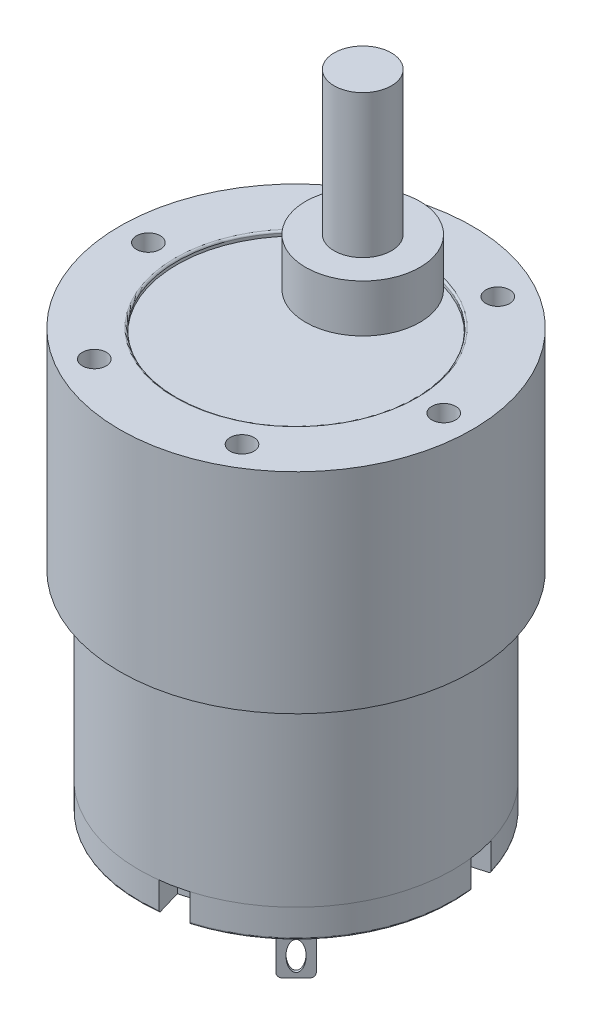
SolidWorks part; units mm, degrees
ref_plane "前视" through (0, 0, 0) normal (0, 0, 1) x (1, 0, 0)
ref_plane "上视" through (0, 0, 0) normal (0, 1, 0) x (1, 0, 0)
ref_plane "右视" through (0, 0, 0) normal (1, 0, 0) x (0, 0, -1)
sketch "草图1" plane through (0, 0, 0) normal (0, 0, 1) x (1, 0, 0)
  line L0 (0, -0.5) -> (0, -44)
  line L1 (16.5, -41) -> (16.48, -41)
  line L2 (16.5, -41) -> (16.5, -22)
  line L5 (16.5, -22) -> (18.5, -22)
  line L6 (18.5, -22) -> (18.5, 0)
  line L7 (18.5, 0) -> (12.7, 0)
  line L8 (12.5, -0.2) -> (12.5, -0.5)
  line L9 (12.5, -0.5) -> (0, -0.5)
  line L10 (16.48, -41) -> (16.48, -43.8)
  line L11 (16.28, -44) -> (0, -44)
  arc A0 (16.48, -43.8) -> (16.28, -44) centre (16.28, -43.8) cw
  arc A1 (12.5, -0.2) -> (12.7, 0) centre (12.7, -0.2) cw
  point P3 (16.5, -18.6359)
  point P4 (16.2721, -41.5113)
  point P6 (16.48, -44)
  dimension "D8" = 0.2
  dimension "D14" = 0.2
  dimension "D2" = 19
  dimension "D3" = 3
  dimension "D4" = 0.02
  dimension "D5" = 18.5
  dimension "D6" = 16.5
  dimension "D7" = 22
  dimension "D11" = 0.5
  dimension "D12" = 12.5
revolve "旋转1" add sketch "草图1" angle 360 about L0
hole_wizard "M3 螺纹孔1" positions "草图3" profile "草图2" tap size "M3" standard "GB"
sketch "草图3" plane through (0, 0, 0) normal (0, 1, 0) x (1, 0, 0)
  line L0 (18.5, 0) -> (-18.5, 0) construction
  circle A0 centre (0, 0) radius 18.5 construction
  circle A1 centre (0, 0) radius 15.5 construction
  point P0 (-15.5, 0)
  dimension "D1" = 31
sketch "草图2" plane through (-15.5, 0, 0) normal (1, 0, 0) x (0, 0, 1)
  line L0 (0, 0) -> (0, 9.2511)
  line L1 (0, 9.2511) -> (1.25, 8.5)
  line L2 (1.25, 8.5) -> (1.25, 0)
  line L5 (1.25, 0) -> (0, 0)
  line L10 (0, 9.2511) -> (-1.25, 8.5) construction
  line L11 (0, -6.35) -> (0, 107.95) construction
  dimension "螺纹孔钻头直径" = 2.5
  dimension "螺纹孔钻头深度" = 8.5
  dimension "导头角度" = 118
cosmetic thread "孔螺蚊线1" parameters "D1"=6, "D2"=3
pattern_circular "阵列(圆周)1" count 6 over 360 about axis through (0, 0, 0) along (0, 1, 0) of "M3 螺纹孔1"
sketch "草图4" plane through (0, 0, 0) normal (0, 1, 0) x (1, 0, 0)
  line L0 (0, 18.5) -> (0, -18.5) construction
  line L1 (-18.5, 0) -> (18.5, 0) construction
  circle A0 centre (0, 0) radius 18.5 construction
  circle A1 centre (0, 7) radius 6
  dimension "D1" = 12
  dimension "D2" = 7
extrude "凸台-拉伸1" add sketch "草图4" along normal blind 5
sketch "草图5" plane through (0, 5, 0) normal (0, 1, 0) x (1, 0, 0)
  circle A0 centre (0, 7) radius 3
  dimension "D1" = 6
extrude "凸台-拉伸2" add sketch "草图5" along normal blind 15
sketch "草图6" plane through (0, -44, 0) normal (0, -1, 0) x (1, 0, 0)
  circle A0 centre (0, 0) radius 3.75
  dimension "D1" = 7.5
extrude "凸台-拉伸3" add sketch "草图6" along normal blind 3
sketch "草图7" plane through (0, -47, 0) normal (0, -1, 0) x (1, 0, 0)
  circle A0 centre (0, 0) radius 1
  dimension "D1" = 2
extrude "凸台-拉伸4" add sketch "草图7" along normal blind 7
sketch "草图8" plane through (0, -44, 0) normal (0, -1, 0) x (1, 0, 0)
  line L0 (-18.5, 0) -> (18.5, 0) construction
  line L1 (0, 18.5) -> (0, -18.5) construction
  line L2 (-4.6748, -15.8031) -> (-3.8142, -12.8938)
  line L3 (-3.8142, -12.8938) -> (-1.2008, -13.6669)
  line L4 (-1.2008, -13.6669) -> (-1.997, -16.3586)
  circle A0 centre (0, 0) radius 18.5 construction
  arc A3 (-4.6748, -15.8031) -> (-1.997, -16.3586) centre (0, 0) ccw
extrude "切除-拉伸1" cut sketch "草图8" against normal blind 3
pattern_circular "阵列(圆周)2" count 4 over 360 about axis through (0, 0, 0) along (0, 1, 0) of "切除-拉伸1"
sketch "草图9" plane through (0, -44, 0) normal (0, -1, 0) x (1, 0, 0)
  line L0 (-8.4853, -8.4853) -> (8.4853, 8.4853) construction
  line L1 (0, 0) -> (13.0815, -13.0815) construction
  line L2 (0, -18.6657) -> (0, 18.5) construction
  line L3 (-9.4399, -7.3186) -> (-7.3186, -9.4399)
  line L4 (-7.3186, -9.4399) -> (-7.5307, -9.652)
  line L5 (-7.5307, -9.652) -> (-9.652, -7.5307)
  line L6 (-9.652, -7.5307) -> (-9.4399, -7.3186)
  line L7 (-9.5459, -7.4246) -> (-7.4246, -9.5459) construction
  line L8 (7.5307, 9.652) -> (7.3186, 9.4399)
  line L9 (9.652, 7.5307) -> (7.5307, 9.652)
  line L10 (9.4399, 7.3186) -> (9.652, 7.5307)
  line L11 (7.3186, 9.4399) -> (9.4399, 7.3186)
  circle A0 centre (0, 0) radius 18.5 construction
  dimension "D1" = 3
  dimension "D2" = 0.3
  dimension "D3" = 24
  dimension "D4" = 45
extrude "凸台-拉伸5" add sketch "草图9" along normal blind 6.5
sketch "草图10" plane through (-8.5913, 0, -8.5913) normal (-0.7071, 0, -0.7071) x (-0.7071, 0, 0.7071)
  line L0 (-1.5, -50.5) -> (1.5, -50.5) construction
  line L1 (1.5, -50.5) -> (-1.5, -50.5) construction
  line L2 (0, -50.5) -> (0, -44) construction
  line L3 (1.5, -44) -> (-1.5, -44) construction
  ellipse E0 centre (0, -48.5) end of major axis (0, -50) minor radius 0.75
  dimension "D1" = 3
  dimension "D2" = 1.5
  dimension "D3" = 3
extrude "切除-拉伸2" cut sketch "草图10" against normal blind 3
fillet "圆角1" radius 0.5 4 edges at (-9.5459, -50.5, -7.4246) (-7.4246, -50.5, -9.5459) (7.4246, -50.5, 9.5459) (9.5459, -50.5, 7.4246)
ref_plane "基准面1" through (0, 0, 0) normal (-0.7071, 0, -0.7071) x (-0.7071, 0, 0.7071)
mirror "镜向5" about plane through (0, 0, 0) normal (-0.7071, 0, -0.7071) of "切除-拉伸2"
ref_plane "基准面2" [suppressed] through (0, -45, 0) normal (0, -1, 0) x (-1, 0, 0)
sketch "草图11" [suppressed] plane through (0, -45, 0) normal (0, -1, 0) x (-1, 0, 0)
  circle A0 centre (0, 0) radius 16.5
  circle A1 centre (0, 0) radius 4
  dimension "D1" = 33
  dimension "D2" = 8
extrude "凸台-拉伸6" [suppressed] add sketch "草图11" along normal blind 1.5
sketch "草图12" [suppressed] plane through (0, -46.5, 0) normal (0, -1, 0) x (1, 0, 0)
  line L0 (-8.3792, -8.3792) -> (8.3792, 8.3792) construction
  line L1 (-7.6721, -9.0863) -> (-9.0863, -7.6721) construction
  line L2 (7.3186, 9.4399) -> (9.4399, 7.3186) construction
  line L3 (-13.0815, 13.0815) -> (0, 0) construction
  line L4 (-12.7279, 0.7071) -> (-0.7071, 12.7279)
  line L5 (-0.7071, 12.7279) -> (-5.6569, 17.6777)
  line L6 (-5.6569, 17.6777) -> (-17.6777, 5.6569)
  line L7 (-17.6777, 5.6569) -> (-12.7279, 0.7071)
  circle A0 centre (0, 0) radius 18.5 construction
  point P15 (-8.3792, 18.5)
  dimension "D1" = 90
  dimension "D2" = 7
  dimension "D3" = 17
  dimension "D4" = 16.5
extrude "凸台-拉伸7" [suppressed] add sketch "草图12" along normal blind 6
sketch "草图13" [suppressed] plane through (-11.6673, 0, 11.6673) normal (-0.7071, 0, 0.7071) x (0.7071, 0, 0.7071)
  line L0 (-8.5, -49.5) -> (8.5, -49.5) construction
  line L1 (-8.5, -52.5) -> (-8.5, -46.5) construction
  line L2 (8.5, -52.5) -> (8.5, -46.5) construction
  line L3 (0, -52.5) -> (0, -46.5) construction
  line L4 (8.5, -52.5) -> (-8.5, -52.5) construction
  line L6 (-8.3, -46.7) -> (8.3, -46.7)
  line L7 (-8.3, -46.7) -> (-8.3, -52.3)
  line L8 (-8.3, -52.3) -> (8.3, -52.3)
  line L9 (8.3, -46.7) -> (8.3, -52.3)
  line L10 (-8.3, -46.7) -> (8.3, -52.3) construction
  line L11 (-8.3, -52.3) -> (8.3, -46.7) construction
  point P11 (0, -49.5)
  dimension "D1" = 0.2
  dimension "D2" = 0.2
extrude "切除-拉伸3" [suppressed] cut sketch "草图13" against normal blind 6
sketch "草图14" [suppressed] plane through (-7.4246, 0, 7.4246) normal (-0.7071, 0, 0.7071) x (0.7071, 0, 0.7071)
  line L0 (-8.3, -49.5) -> (8.3, -49.5) construction
  line L1 (-8.3, -46.7) -> (-8.3, -52.3) construction
  line L2 (8.3, -52.3) -> (8.3, -46.7) construction
  line L3 (0, -46.7) -> (0, -52.3) construction
  line L4 (8.3, -46.7) -> (-8.3, -46.7) construction
  line L5 (-8.3, -52.3) -> (8.3, -52.3) construction
  circle A0 centre (-7.5, -49.5) radius 0.25
  circle A1 centre (-4.5, -49.5) radius 0.25
  circle A2 centre (-1.5, -49.5) radius 0.25
  circle A3 centre (7.5, -49.5) radius 0.25
  circle A4 centre (4.5, -49.5) radius 0.25
  circle A5 centre (1.5, -49.5) radius 0.25
  dimension "D1" = 0.5
  dimension "D2" = 3
  dimension "D3" = 3
  dimension "D4" = 3
extrude "凸台-拉伸8" [suppressed] add sketch "草图14" along normal blind 6
sketch "草图15" [suppressed] plane through (0, -47, 0) normal (0, -1, 0) x (1, 0, 0)
  circle A0 centre (0, 0) radius 7
  dimension "D1" = 14
extrude "凸台-拉伸9" [suppressed] add sketch "草图15" along normal blind 6
sketch "草图16" [suppressed] plane through (0, -46.5, 0) normal (0, -1, 0) x (1, 0, 0)
  line L0 (-11.6673, 11.6673) -> (0, 0) construction
  line L1 (-5.6569, 17.6777) -> (-17.6777, 5.6569) construction
  line L2 (0, 0) -> (11.6673, -11.6673) construction
  line L3 (1.2542, -8.6049) -> (0.8203, -7.704)
  line L4 (0.8203, -7.704) -> (4.424, -5.9681)
  line L5 (4.424, -5.9681) -> (4.858, -6.8691)
  line L6 (4.858, -6.8691) -> (1.2542, -8.6049)
  line L7 (5.9681, -4.424) -> (6.8691, -4.858)
  line L8 (8.6049, -1.2542) -> (7.704, -0.8203)
  line L9 (7.704, -0.8203) -> (5.9681, -4.424)
  line L10 (6.8691, -4.858) -> (8.6049, -1.2542)
  arc A0 (-16.0104, 3.9896) -> (-3.9896, 16.0104) centre (0, 0) ccw construction
  point P12 (1.7759, -9.592)
  point P14 (1.4413, -8.8855)
  point P15 (0.7719, -8.5136)
  point P16 (1.2542, -8.6049)
  dimension "D1" = 90
  dimension "D2" = 4
  dimension "D3" = 1
extrude "凸台-拉伸10" [suppressed] add sketch "草图16" along normal blind 4
